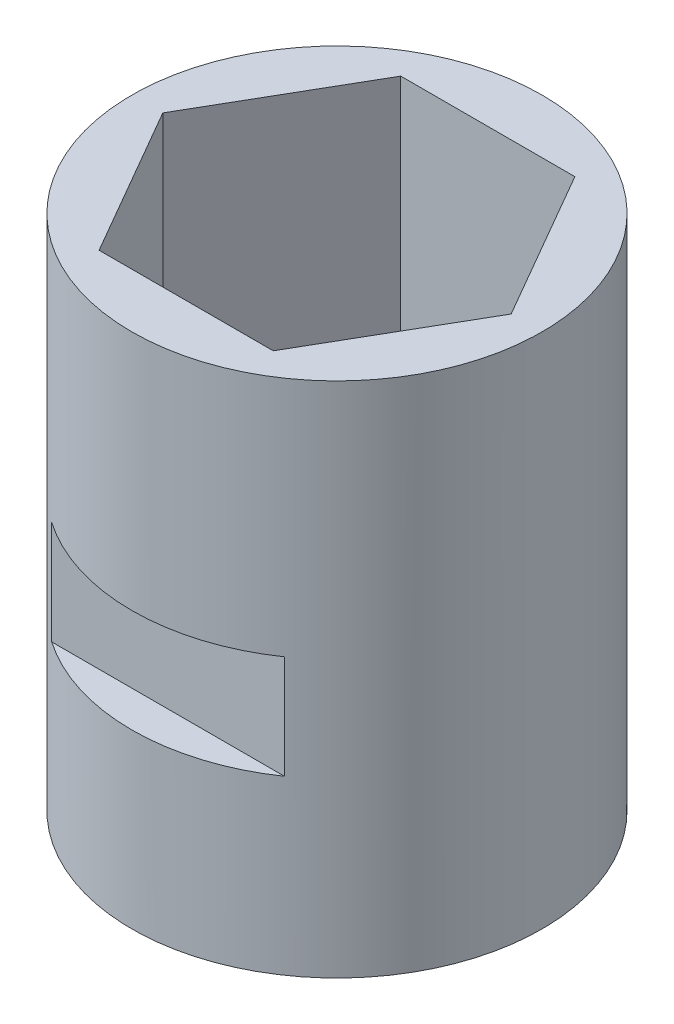
SolidWorks part; units mm, degrees
material "Polyester Resin"
ref_plane "Front Plane" through (0, 0, 0) normal (0, 0, 1) x (1, 0, 0)
ref_plane "Top Plane" through (0, 0, 0) normal (0, 1, 0) x (1, 0, 0)
ref_plane "Right Plane" through (0, 0, 0) normal (1, 0, 0) x (0, 0, -1)
sketch "Sketch1" plane through (0, 0, 0) normal (0, 1, 0) x (1, 0, 0)
  line L1 (-3.2079, 5.5563) -> (-6.4158, 0)
  line L2 (-6.4158, 0) -> (-3.2079, -5.5562)
  line L3 (-3.2079, -5.5562) -> (3.2079, -5.5562)
  line L4 (3.2079, -5.5562) -> (6.4158, 0)
  line L5 (6.4158, 0) -> (3.2079, 5.5563)
  line L6 (3.2079, 5.5563) -> (-3.2079, 5.5563)
  circle A0 centre (0, 0) radius 5.5562 construction
  circle A1 centre (0, 0) radius 7.5565
  dimension "D2" = 15.113
  dimension "D1" = 11.1125
extrude "Boss-Extrude1" add sketch "Sketch1" along normal blind 15.875
sketch "Sketch2" plane through (0, 0, 0) normal (0, -1, 0) x (1, 0, 0)
  circle A0 centre (0, 0) radius 7.5565
  circle A1 centre (0, 0) radius 3.3782
  dimension "D1" = 6.7564
extrude "Boss-Extrude2" add sketch "Sketch2" along normal blind 3.175
sketch "Sketch3" plane through (0, 0, 0) normal (1, 0, 0) x (0, 0, -1)
  line L0 (-6.223, 6.985) -> (-6.223, 3.175)
  line L1 (6.223, 6.985) -> (6.223, 3.175)
  line L2 (-7.5565, -3.175) -> (7.5565, -3.175) construction
  line L3 (-6.223, 6.985) -> (-8.202, 6.985)
  line L4 (-8.202, 6.985) -> (-8.202, 3.175)
  line L5 (-8.202, 3.175) -> (-6.223, 3.175)
  line L6 (6.223, 6.985) -> (8.4791, 6.985)
  line L7 (8.4791, 6.985) -> (8.4791, 3.175)
  line L8 (8.4791, 3.175) -> (6.223, 3.175)
  dimension "D1" = 12.446
  dimension "D2" = 6.223
  dimension "D3" = 3.81
  dimension "D4" = 3.81
  dimension "D5" = 6.35
  dimension "D6" = 6.35
extrude "Cut-Extrude1" cut sketch "Sketch3" against normal through all and the other way through all
